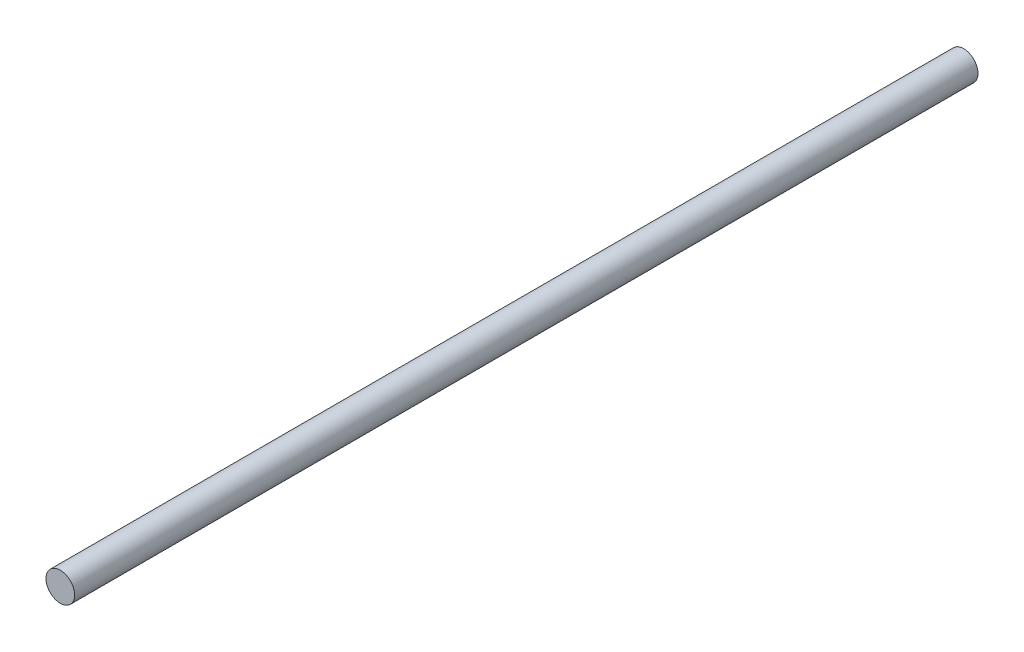
SolidWorks part; units mm, degrees
ref_plane "Front Plane" through (0, 0, 0) normal (1, 0, 0) x (0, 1, 0)
ref_plane "Top Plane" through (0, 0, 0) normal (0, 0, 1) x (0, 1, 0)
ref_plane "Right Plane" through (0, 0, 0) normal (0, 1, 0) x (-1, 0, 0)
sketch "Sketch1" plane through (0, 0, 0) normal (0, 0, 1) x (0, 1, 0)
  circle A0 centre (0, 0) radius 5
  dimension "D1" = 10
extrude "Boss-Extrude1" add sketch "Sketch1" along normal blind 315
sketch "Sketch2" plane through (0, 0, 0) normal (0, 1, 0) x (-1, 0, 0)
  line L0 (0, 0) -> (0, 315) construction
  line L1 (5, 315) -> (-5, 315) construction
